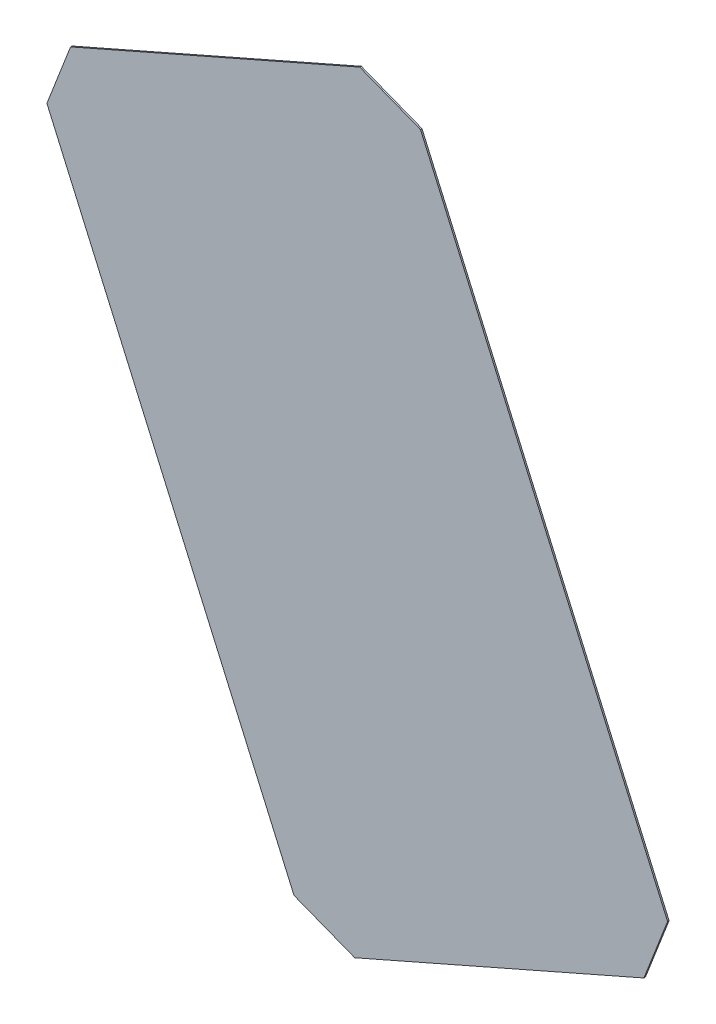
SolidWorks part; units mm, degrees
material "6061-T6 (SS)"
ref_plane "Front Plane" through (0, 0, 0) normal (0, 0, 1) x (1, 0, 0)
ref_plane "Top Plane" through (0, 0, 0) normal (0, 1, 0) x (1, 0, 0)
ref_plane "Right Plane" through (0, 0, 0) normal (1, 0, 0) x (0, 0, -1)
sketch "Sketch1" plane through (0, 0, 0) normal (0, 0, 1) x (1, 0, 0)
  line L8 (-89.3397, 491.3905) -> (98.984, 574.1352)
  line L9 (98.984, 574.1352) -> (138.5175, 558.7372)
  line L10 (138.5175, 558.7372) -> (299.4212, 192.5269)
  line L11 (299.4212, 192.5269) -> (284.0232, 152.9933)
  line L12 (284.0232, 152.9933) -> (95.6996, 70.2486)
  line L13 (95.6996, 70.2486) -> (56.166, 85.6466)
  line L14 (56.166, 85.6466) -> (-104.7377, 451.8569)
  line L15 (-104.7377, 451.8569) -> (-89.3397, 491.3905)
  dimension "D1" = 460
  dimension "D2" = 265.7
extrude "Boss-Extrude1" add sketch "Sketch1" along normal blind 1
